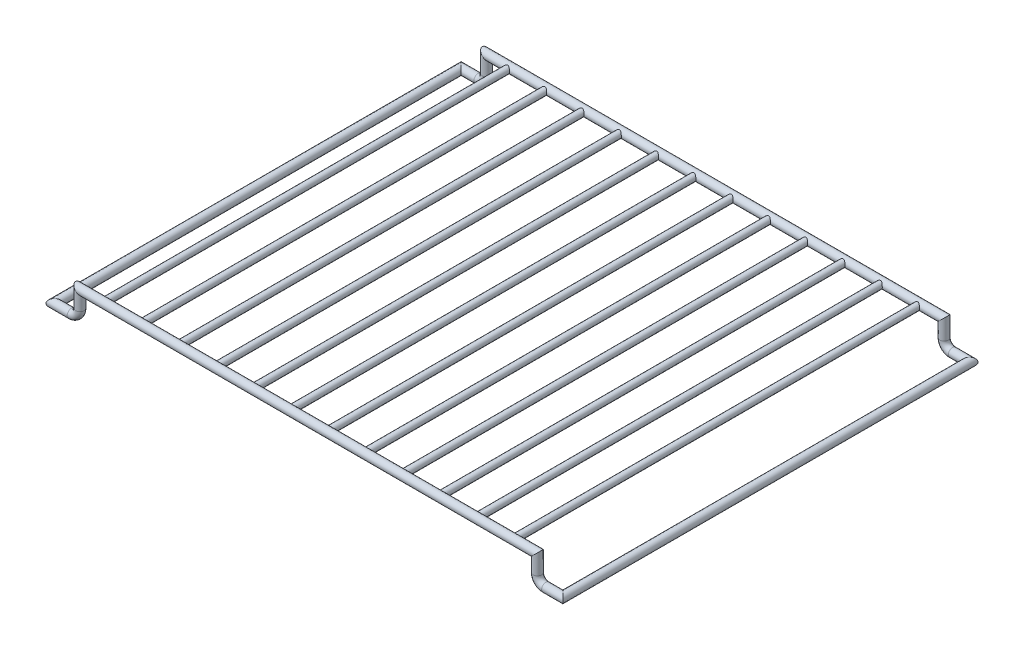
SolidWorks part; units mm, degrees
ref_plane "Front Plane" through (0, 0, 0) normal (0, 0, 1) x (1, 0, 0)
ref_plane "Top Plane" through (0, 0, 0) normal (0, 1, 0) x (1, 0, 0)
ref_plane "Right Plane" through (0, 0, 0) normal (1, 0, 0) x (0, 0, -1)
sketch3d "3DSketch1"
  line L0 (0, 0, 0) -> (135, 0, 0)
  line L1 (135, 0, 0) -> (135, -10, 0)
  line L2 (140, -15, 0) -> (150, -15, 0)
  line L3 (150, -15, 0) -> (150, -15, -240)
  line L4 (150, -15, -240) -> (140, -15, -240)
  line L5 (135, -10, -240) -> (135, 0, -240)
  line L6 (135, 0, -240) -> (0, 0, -240)
  arc A0 (135, -10, 0) -> (140, -15, 0) centre (140, -10, 0) ccw
  arc A1 (140, -15, -240) -> (135, -10, -240) centre (140, -10, -240) ccw
  point P11 (135, -15, 0)
  point P12 (140, -10, 5)
  point P15 (135, -15, -240)
  point P16 (140, -10, -245)
  dimension "D8" = 5
  dimension "D1" = 135
  dimension "D2" = 15
  dimension "D3" = 15
  dimension "D4" = 240
  dimension "D5" = 15
  dimension "D6" = 15
  dimension "D7" = 135
sketch "Sketch1" plane through (0, 0, 0) normal (1, 0, 0) x (0, 0, -1)
  circle A0 centre (0, 0) radius 2.5
  dimension "D1" = 5
sweep "Sweep1" add profiles "Sketch1" path "3DSketch1"
sketch "Sketch2" plane through (0, 0, 0) normal (0, 0, 1) x (1, 0, 0)
  line L0 (83.875, 0) -> (-83.875, 0) construction
  circle A0 centre (11, 0) radius 2
  dimension "D2" = 4
  dimension "D1" = 11
extrude "Boss-Extrude1" add sketch "Sketch2" against normal up to surface (237.5 mm away)
pattern_linear "LPattern1" count 6 spacing 22 along (1, 0, 0) of "Boss-Extrude1"
mirror "Mirror1" about plane through (0, 0, -240) normal (-1, 0, 0) of bodies 103
